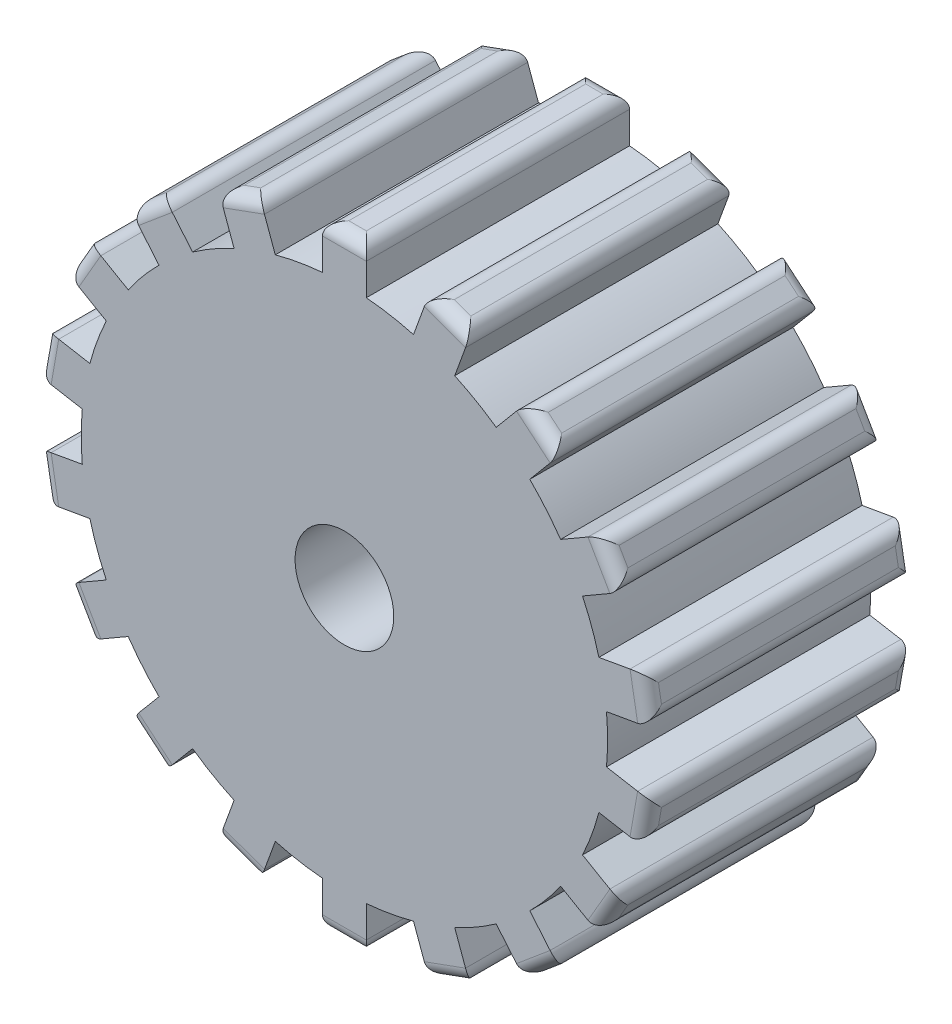
SolidWorks part; units mm, degrees
ref_plane "Front Plane" through (0, 0, 0) normal (0, 0, 1) x (1, 0, 0)
ref_plane "Top Plane" through (0, 0, 0) normal (0, 1, 0) x (1, 0, 0)
ref_plane "Right Plane" through (0, 0, 0) normal (1, 0, 0) x (0, 0, -1)
sketch "Sketch2" plane through (0, 0, 0) normal (0, 0, 1) x (1, 0, 0)
  circle A0 centre (0, 0) radius 60
extrude "Boss-Extrude1" add sketch "Sketch2" along normal blind 60
sketch "Sketch3" plane through (0, 0, 60) normal (0, 0, 1) x (1, 0, 0)
  line L0 (0, 60) -> (0, 70) construction
  line L1 (5, 70) -> (-5, 70)
  line L2 (-5, 70) -> (-5, 59.5215)
  line L3 (-5, 59.5215) -> (5, 59.5215)
  line L4 (5, 59.5215) -> (5, 70)
  circle A0 centre (0, 0) radius 60 construction
  point P9 (0, 70)
extrude "Boss-Extrude2" add sketch "Sketch3" against normal blind 60
fillet "Fillet2" radius 3 4 edges at (-5, 70, 30) (0, 70, 60) (0, 70, 0) (5, 70, 30)
pattern_circular "CirPattern1" count 18 over 360 about axis through (0, 0, 0) along (0, 0, 1) of "Fillet2", "Boss-Extrude2"
sketch "Sketch4" plane through (0, 0, 60) normal (0, 0, 1) x (1, 0, 0)
  circle A0 centre (0, 0) radius 10
extrude "Cut-Extrude1" cut sketch "Sketch4" against normal blind 60
sketch "Sketch5" plane through (0, 0, 0) normal (0, 0, -1) x (-1, 0, 0)
  circle A0 centre (0, 0) radius 11.25
extrude "Cut-Extrude2" cut sketch "Sketch5" against normal up to surface (60 mm away) up to face at (10, 0, 60)
